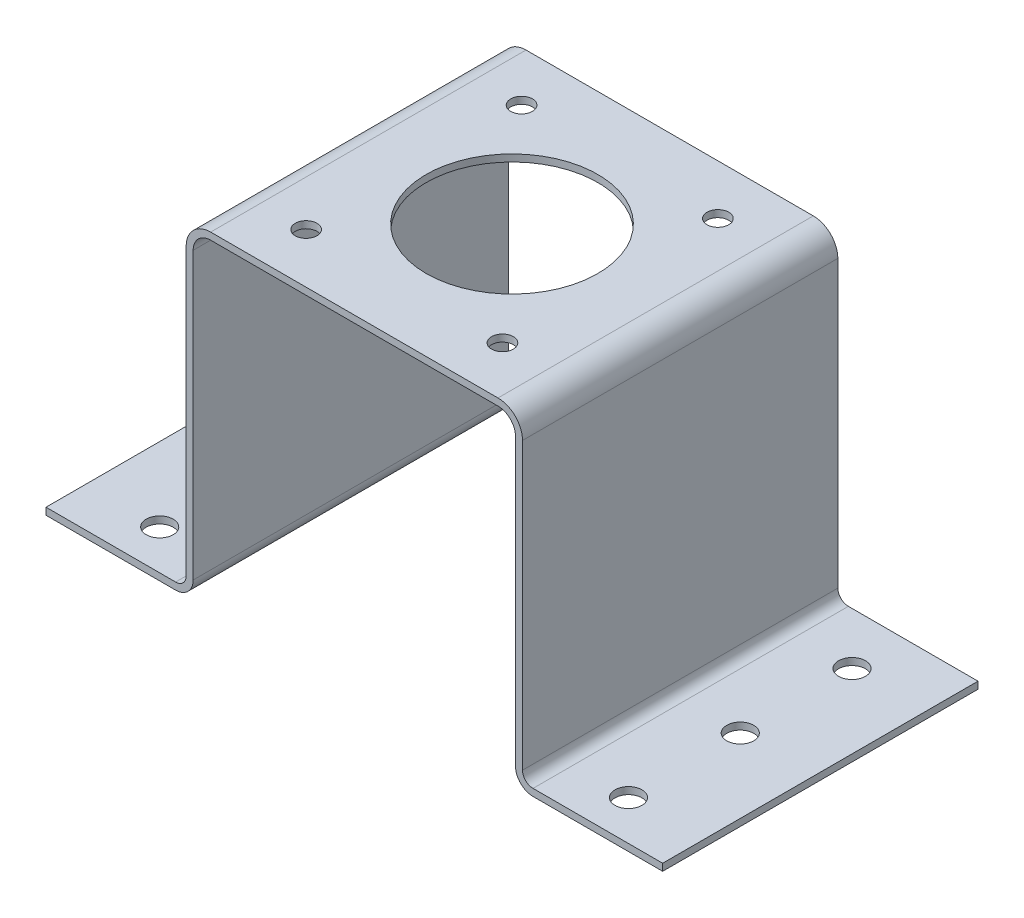
SolidWorks part; units mm, degrees
material "6061 Alloy"
ref_plane "Front Plane" through (0, 0, 0) normal (0, 0, 1) x (1, 0, 0)
ref_plane "Top Plane" through (0, 0, 0) normal (0, 1, 0) x (1, 0, 0)
ref_plane "Right Plane" through (0, 0, 0) normal (1, 0, 0) x (0, 0, -1)
sketch "Sketch1" plane through (0, 0, 0) normal (0, 0, 1) x (1, 0, 0)
  line L0 (0, 0) -> (18.796, 0)
  line L1 (21.336, 2.54) -> (21.336, 43.942)
  line L2 (23.876, 46.482) -> (65.532, 46.482)
  line L3 (68.072, 43.942) -> (68.072, 2.54)
  line L4 (70.612, 0) -> (89.408, 0)
  line L5 (0, 1.016) -> (18.796, 1.016)
  line L6 (20.32, 2.54) -> (20.32, 43.942)
  line L7 (23.876, 47.498) -> (65.532, 47.498)
  line L8 (69.088, 43.942) -> (69.088, 2.54)
  line L9 (70.612, 1.016) -> (89.408, 1.016)
  line L10 (0, 0) -> (0, 1.016)
  line L11 (89.408, 0) -> (89.408, 1.016)
  arc A0 (68.072, 2.54) -> (70.612, 0) centre (70.612, 2.54) ccw
  arc A1 (18.796, 0) -> (21.336, 2.54) centre (18.796, 2.54) ccw
  arc A2 (65.532, 46.482) -> (68.072, 43.942) centre (65.532, 43.942) cw
  arc A3 (21.336, 43.942) -> (23.876, 46.482) centre (23.876, 43.942) cw
  arc A4 (18.796, 1.016) -> (20.32, 2.54) centre (18.796, 2.54) ccw
  arc A5 (20.32, 43.942) -> (23.876, 47.498) centre (23.876, 43.942) cw
  arc A6 (65.532, 47.498) -> (69.088, 43.942) centre (65.532, 43.942) cw
  arc A7 (69.088, 2.54) -> (70.612, 1.016) centre (70.612, 2.54) ccw
  point P5 (0, 0)
  point P12 (21.336, 0)
  point P15 (68.072, 46.482)
  point P18 (21.336, 46.482)
  dimension "D4" = 2.54
  dimension "D5" = 2.54
  dimension "D1" = 21.336
  dimension "D2" = 46.482
  dimension "D3" = 46.736
  dimension "D6" = 1.016
extrude "Boss-Extrude1" add sketch "Sketch1" along normal blind 45.72 contours L6 A5 L7 A6 L8 A7 L9 L11 L4 A0 L3 A2 L2 A3 L1 A1 L0 L10 L5 A4
sketch "Sketch2" plane through (0, 47.498, 0) normal (0, 1, 0) x (1, 0, 0)
  circle A0 centre (44.704, -22.86) radius 12.446
  dimension "D1" = 24.892
extrude "Cut-Extrude1" cut sketch "Sketch2" against normal through all
sketch "Sketch3" plane through (0, 47.498, 0) normal (0, 1, 0) x (1, 0, 0)
  line L0 (65.532, 0) -> (44.704, -22.86) construction
  line L1 (44.704, 0) -> (44.704, -45.72) construction
  line L2 (23.876, 0) -> (65.532, 0) construction
  line L3 (23.876, -45.72) -> (65.532, -45.72) construction
  line L4 (23.876, -22.86) -> (65.532, -22.86) construction
  line L5 (23.876, -45.72) -> (23.876, 0) construction
  line L6 (65.532, -45.72) -> (65.532, 0) construction
  circle A2 centre (58.9367, -7.2387) radius 1.5748
  circle A3 centre (44.704, -22.86) radius 12.446 construction
  circle A4 centre (30.4713, -7.2387) radius 1.5748
  circle A5 centre (58.9367, -38.4813) radius 1.5748
  circle A6 centre (30.4713, -38.4813) radius 1.5748
  point P4 (57.8761, -8.4028)
  point P5 (53.0863, -13.66)
  dimension "D1" = 7.112
  dimension "D2" = 3.1496
extrude "Cut-Extrude2" cut sketch "Sketch3" against normal through all
sketch "Sketch4" plane through (0, 1.016, 0) normal (0, 1, 0) x (1, 0, 0)
  line L0 (10.7188, 0) -> (10.7188, -45.72) construction
  line L1 (0, 0) -> (18.796, 0) construction
  line L2 (0, -45.72) -> (18.796, -45.72) construction
  line L3 (0, -45.72) -> (0, 0) construction
  circle A0 centre (10.7188, -7.5438) radius 1.9558
  circle A1 centre (10.7188, -23.749) radius 1.9558
  circle A2 centre (10.7188, -39.9542) radius 1.9558
  point P6 (10.7188, -5.588)
  point P10 (8.763, -7.5438)
  point P12 (10.7188, -9.4996)
  point P13 (10.7188, -21.7932)
  point P18 (10.7188, -25.7048)
  point P19 (10.7188, -37.9984)
  dimension "D2" = 3.9116
  dimension "D5" = 12.2936
  dimension "D1" = 5.588
  dimension "D3" = 8.763
  dimension "D4" = 12.2936
extrude "Cut-Extrude3" cut sketch "Sketch4" against normal blind 45.72
ref_plane "Plane1" through (44.704, 0, 0) normal (-1, 0, 0) x (0, 0, 1)
mirror "Mirror1" about plane through (44.704, 0, 0) normal (-1, 0, 0) of "Cut-Extrude3"
